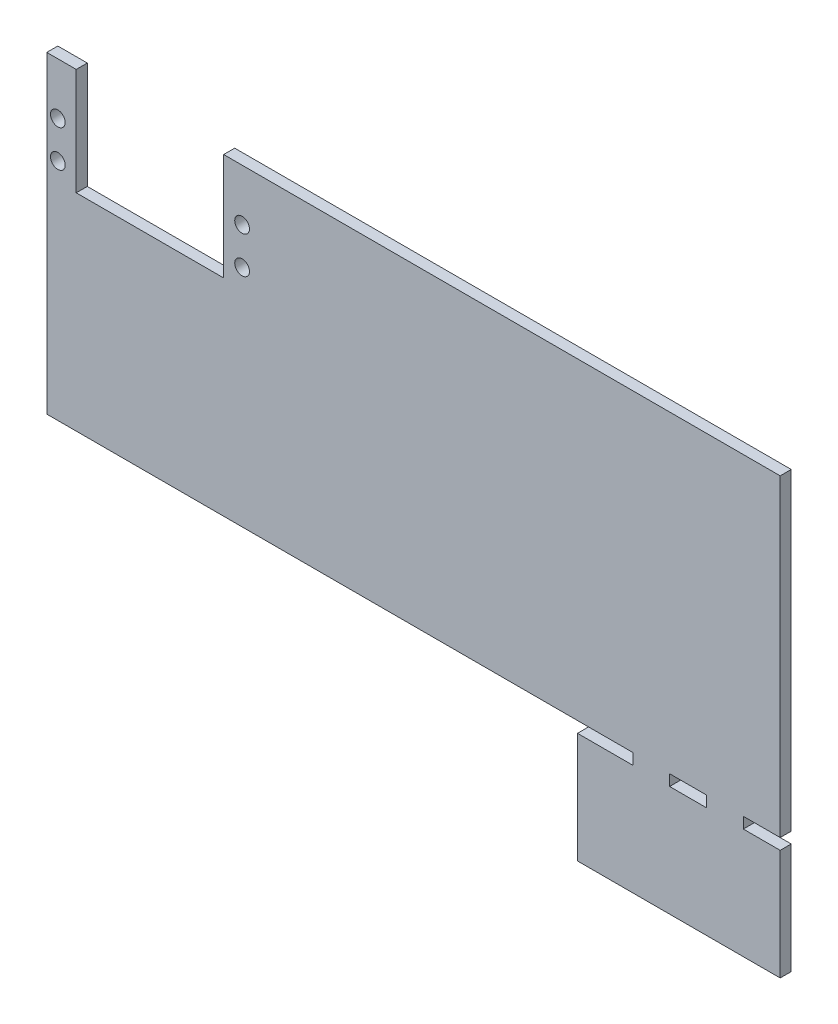
SolidWorks part; units mm, degrees
ref_plane "Front Plane" through (0, 0, 0) normal (0, 0, 1) x (1, 0, 0)
ref_plane "Top Plane" through (0, 0, 0) normal (0, 1, 0) x (1, 0, 0)
ref_plane "Right Plane" through (0, 0, 0) normal (1, 0, 0) x (0, 0, -1)
sketch "Sketch1" plane through (0, 0, 0) normal (0, 0, 1) x (1, 0, 0)
  line L1 (-27.5, -27.5) -> (27.5, -27.5)
  line L2 (-27.5, -27.5) -> (-27.5, 27.5)
  line L3 (-27.5, 27.5) -> (27.5, 27.5)
  line L4 (27.5, -27.5) -> (27.5, 27.5)
  line L5 (0, 27.5) -> (0, -27.5) construction
  line L6 (-27.5, 0) -> (27.5, 0) construction
  point P0 (0, 0)
  dimension "D1" = 55
  dimension "D2" = 55
extrude "Boss-Extrude1" add sketch "Sketch1" along normal blind 3
sketch "Sketch2" plane through (0, 0, 3) normal (0, 0, 1) x (1, 0, 0)
  line L0 (-27.5, -24.5) -> (27.5, -24.5) construction
  line L1 (-27.5, 27.5) -> (-27.5, -27.5) construction
  line L2 (27.5, -27.5) -> (27.5, 27.5) construction
  line L3 (-27.5, -27.5) -> (27.5, -27.5) construction
  line L4 (17.5, -24.5) -> (17.5, -27.5) construction
  line L5 (27.5, -27.5) -> (27.5, 27.5) construction
  line L6 (7.5, -24.5) -> (7.5, -27.5) construction
  line L7 (27.5, -24.5) -> (17.5, -24.5)
  line L8 (27.5, -24.5) -> (27.5, -27.5)
  line L9 (27.5, -27.5) -> (17.5, -27.5)
  line L10 (17.5, -24.5) -> (17.5, -27.5)
  line L11 (-12.5, -24.5) -> (-12.5, -27.5) construction
  line L12 (7.5, -24.5) -> (-2.5, -24.5)
  line L13 (7.5, -24.5) -> (7.5, -27.5)
  line L14 (7.5, -27.5) -> (-2.5, -27.5)
  line L15 (-2.5, -24.5) -> (-2.5, -27.5)
  line L17 (-12.5, -24.5) -> (-27.5, -24.5)
  line L18 (-12.5, -24.5) -> (-12.5, -27.5)
  line L19 (-12.5, -27.5) -> (-27.5, -27.5)
  line L20 (-27.5, -24.5) -> (-27.5, -27.5)
  dimension "D1" = 3
  dimension "D2" = 10
  dimension "D3" = 10
  dimension "D4" = 10
  dimension "D5" = 10
extrude "Cut-Extrude1" cut sketch "Sketch2" against normal blind 3 contours L18 L17 L20 L19 | L13 L12 L15 L14 | L8 L7 L10 L9
sketch "Sketch3" plane through (0, 0, 0) normal (0, 0, -1) x (-1, 0, 0)
  line L0 (-27.5, -24.5) -> (-27.5, -90.5) construction
  line L1 (27.5, -24.5) -> (27.5, -57.5) construction
  line L2 (27.5, -57.5) -> (-27.5, -57.5) construction
  line L3 (-7.5, -27.5) -> (-17.5, -27.5) construction
  line L5 (27.5, -57.5) -> (-27.5, -57.5)
  line L6 (27.5, -57.5) -> (27.5, -27.5)
  line L7 (27.5, -27.5) -> (-27.5, -27.5)
  line L8 (-27.5, -57.5) -> (-27.5, -27.5)
  dimension "D1" = 30
extrude "Boss-Extrude2" add sketch "Sketch3" against normal blind 3
sketch "Sketch4" plane through (0, 0, 0) normal (0, 0, -1) x (-1, 0, 0)
  line L0 (-27.5, 27.5) -> (171.5, 27.5) construction
  line L4 (27.5, -24.5) -> (171.5, -24.5)
  line L5 (27.5, -24.5) -> (27.5, 27.5)
  line L6 (27.5, 27.5) -> (171.5, 27.5)
  line L7 (171.5, -24.5) -> (171.5, 27.5)
  dimension "D1" = 199
extrude "Boss-Extrude3" add sketch "Sketch4" against normal blind 3
sketch "Sketch5" plane through (0, 0, 0) normal (0, 0, -1) x (-1, 0, 0)
  line L0 (-27.5, 27.5) -> (-27.5, 40.5) construction
  line L1 (171.5, 27.5) -> (171.5, 40.5) construction
  line L2 (171.5, 40.5) -> (-27.5, 40.5) construction
  line L3 (12.5, -24.5) -> (171.5, -24.5) construction
  line L4 (-27.5, 27.5) -> (-27.5, 40.5)
  line L5 (-27.5, 40.5) -> (171.5, 40.5)
  line L6 (171.5, 40.5) -> (171.5, 27.5)
  line L7 (171.5, 27.5) -> (-27.5, 27.5)
  dimension "D1" = 65
extrude "Boss-Extrude4" add sketch "Sketch5" against normal blind 3
sketch "Sketch6" plane through (0, 0, 0) normal (0, 0, -1) x (-1, 0, 0)
  line L0 (-27.5, 40.5) -> (-27.5, 60.5) construction
  line L2 (-27.5, 60.5) -> (171.5, 60.5)
  line L3 (-27.5, 60.5) -> (-27.5, 40.5)
  line L4 (-27.5, 40.5) -> (171.5, 40.5)
  line L5 (171.5, 60.5) -> (171.5, 40.5)
  dimension "D1" = 20
extrude "Boss-Extrude5" add sketch "Sketch6" against normal blind 3
sketch "Sketch7" plane through (0, 0, 0) normal (0, 0, -1) x (-1, 0, 0)
  line L0 (41.5, 60.5) -> (41.5, -24.5) construction
  line L1 (171.5, 60.5) -> (-27.5, 60.5) construction
  line L2 (12.5, -24.5) -> (171.5, -24.5) construction
  line L3 (171.5, -24.5) -> (171.5, 60.5) construction
  line L4 (41.5, 25.5) -> (171.5, 25.5) construction
  line L5 (123.5, 41.5) -> (184.4312, 41.5) construction
  line L6 (123.5, 51.5) -> (163.5, 51.5)
  line L7 (123.5, 51.5) -> (123.5, 31.5)
  line L8 (123.5, 31.5) -> (163.5, 31.5)
  line L9 (163.5, 51.5) -> (163.5, 31.5)
  line L10 (168.5, 47.6633) -> (168.5, 37.884) construction
  line L11 (168.5, 37.884) -> (168.5, 28.4787) construction
  line L12 (168.5, 47.6633) -> (168.5, 56.16) construction
  line L13 (163.5, 46.5) -> (168.5, 46.5) construction
  line L14 (143.5, 31.5) -> (143.5, 51.5) construction
  circle A0 centre (168.5, 46.5) radius 2
  circle A1 centre (168.5, 36.5) radius 2
  circle A2 centre (118.5, 36.5) radius 2
  circle A3 centre (118.5, 46.5) radius 2
  dimension "D1" = 130
  dimension "D2" = 50
  dimension "D3" = 20
  dimension "D4" = 40
  dimension "D5" = 6
  dimension "D6" = 8
  dimension "D7" = 5
  dimension "D8" = 5
extrude "Cut-Extrude22" cut sketch "Sketch7" against normal blind 33 contours L7 L6 L9 L8 | A0 | A1 | A2 | A3
sketch "Sketch8" plane through (0, 0, 0) normal (0, 0, -1) x (-1, 0, 0)
  line L0 (123.5, 51.5) -> (123.5, 60.5) construction
  line L1 (171.5, 60.5) -> (-27.5, 60.5) construction
  line L3 (163.5, 51.5) -> (123.5, 51.5)
  line L4 (163.5, 51.5) -> (163.5, 60.5)
  line L5 (163.5, 60.5) -> (123.5, 60.5)
  line L6 (123.5, 51.5) -> (123.5, 60.5)
extrude "Cut-Extrude23" cut sketch "Sketch8" against normal blind 33
